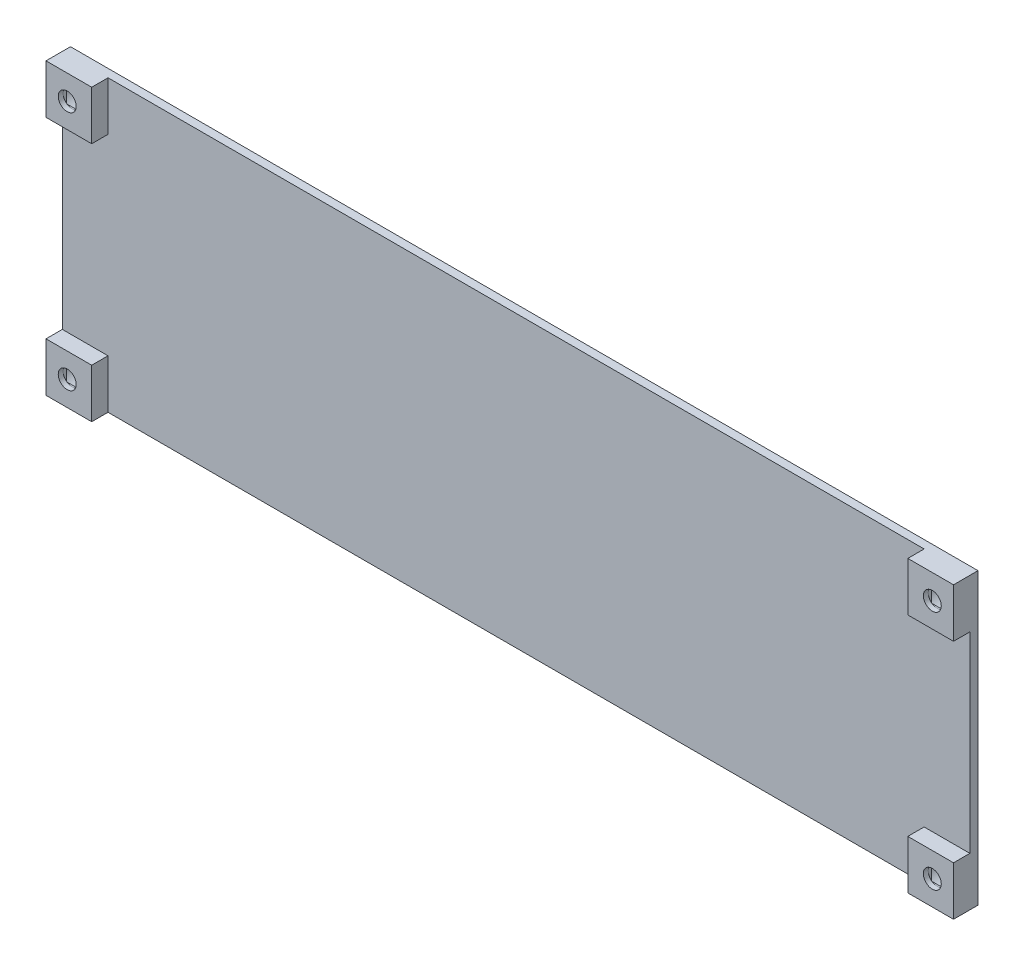
SolidWorks part; units mm, degrees
ref_plane "Front Plane" through (0, 0, 0) normal (0, 0, 1) x (1, 0, 0)
ref_plane "Top Plane" through (0, 0, 0) normal (0, 1, 0) x (1, 0, 0)
ref_plane "Right Plane" through (0, 0, 0) normal (1, 0, 0) x (0, 0, -1)
sketch "Sketch1" plane through (0, 0, 0) normal (0, 0, 1) x (1, 0, 0)
  line L1 (-56, -17.75) -> (56, -17.75)
  line L2 (-56, -17.75) -> (-56, 17.75)
  line L3 (-56, 17.75) -> (56, 17.75)
  line L4 (56, -17.75) -> (56, 17.75)
  line L5 (-56, -17.75) -> (56, 17.75) construction
  line L6 (-56, 17.75) -> (56, -17.75) construction
  point P0 (0, 0)
  dimension "D1" = 112
  dimension "D2" = 35.5
extrude "Boss-Extrude1" add sketch "Sketch1" along normal blind 1
sketch "Sketch2" plane through (0, 0, 1) normal (0, 0, 1) x (1, 0, 0)
  line L0 (0, -17.75) -> (0, 17.75) construction
  line L1 (-56, 17.75) -> (-50, 17.75)
  line L2 (-56, 17.75) -> (-56, 11.75)
  line L3 (-56, 11.75) -> (-50, 11.75)
  line L4 (-50, 17.75) -> (-50, 11.75)
  line L5 (-56, -17.75) -> (56, -17.75) construction
  line L6 (56, 17.75) -> (-56, 17.75) construction
  line L7 (-56, 0) -> (56, 0) construction
  line L8 (-56, 17.75) -> (-56, -17.75) construction
  line L9 (56, -17.75) -> (56, 17.75) construction
  line L10 (-50, -17.75) -> (-50, -11.75)
  line L11 (-56, -11.75) -> (-50, -11.75)
  line L12 (-56, -17.75) -> (-56, -11.75)
  line L13 (-56, -17.75) -> (-50, -17.75)
  line L14 (56, -17.75) -> (50, -17.75)
  line L15 (56, -17.75) -> (56, -11.75)
  line L16 (56, -11.75) -> (50, -11.75)
  line L17 (50, -17.75) -> (50, -11.75)
  line L18 (50, 17.75) -> (50, 11.75)
  line L19 (56, 11.75) -> (50, 11.75)
  line L20 (56, 17.75) -> (56, 11.75)
  line L21 (56, 17.75) -> (50, 17.75)
  dimension "D1" = 6
extrude "Boss-Extrude2" add sketch "Sketch2" along normal blind 2
sketch "Sketch3" plane through (0, 0, 3) normal (0, 0, 1) x (1, 0, 0)
  line L0 (-56, 0) -> (56, 0) construction
  line L1 (-56, 11.75) -> (-56, -11.75) construction
  line L2 (56, -11.75) -> (56, 11.75) construction
  line L3 (0, 17.75) -> (0, -17.75) construction
  line L4 (50, 17.75) -> (-50, 17.75) construction
  line L5 (-50, -17.75) -> (50, -17.75) construction
  line L6 (-56, 11.75) -> (-50, 17.75) construction
  line L7 (-56, -11.75) -> (-50, -17.75) construction
  line L8 (56, -11.75) -> (50, -17.75) construction
  line L9 (56, 11.75) -> (50, 17.75) construction
  circle A0 centre (-53, 14.75) radius 1.1
  circle A1 centre (-53, -14.75) radius 1.1
  circle A2 centre (53, -14.75) radius 1.1
  circle A3 centre (53, 14.75) radius 1.1
  dimension "D1" = 2.2
extrude "Cut-Extrude1" cut sketch "Sketch3" against normal through all
sketch "Sketch4" plane through (0, 0, 0) normal (0, 0, -1) x (-1, 0, 0)
  circle A0 centre (-53, 14.75) radius 2
  circle A1 centre (-53, -14.75) radius 2
  circle A2 centre (53, 14.75) radius 2
  circle A3 centre (53, -14.75) radius 2
  dimension "D1" = 4
extrude "Cut-Extrude2" cut sketch "Sketch4" against normal blind 2
sketch "Sketch5" plane through (0, 0, 2) normal (0, 0, -1) x (-1, 0, 0)
  line L2 (-54.1, 13.0797) -> (-54.1, 16.4203)
  line L4 (-51.9, 13.0797) -> (-51.9, 16.4203)
  line L5 (-54.1, 13.0797) -> (-51.9, 16.4203) construction
  line L6 (-54.1, 16.4203) -> (-51.9, 13.0797) construction
  circle A0 centre (-53, 14.75) radius 2 construction
  circle A1 centre (-53, 14.75) radius 1.1 construction
  circle A2 centre (-53, 14.75) radius 2 construction
  arc A3 (-51.9, 16.4203) -> (-54.1, 16.4203) centre (-53, 14.75) ccw
  arc A4 (-54.1, 13.0797) -> (-51.9, 13.0797) centre (-53, 14.75) ccw
  point P0 (-53, 14.75)
extrude "Cut-Extrude3" cut sketch "Sketch5" against normal blind 0.2
sketch "Sketch6" plane through (0, 0, 2.2) normal (0, 0, -1) x (-1, 0, 0)
  line L0 (-51.9, 13.0797) -> (-51.9, 16.4203) construction
  line L1 (-54.1, 13.65) -> (-51.9, 13.65)
  line L2 (-54.1, 13.65) -> (-54.1, 15.85)
  line L3 (-54.1, 15.85) -> (-51.9, 15.85)
  line L4 (-51.9, 13.65) -> (-51.9, 15.85)
  line L5 (-54.1, 13.65) -> (-51.9, 15.85) construction
  line L6 (-54.1, 15.85) -> (-51.9, 13.65) construction
  arc A0 (-51.9, 14.75) -> (-54.1, 14.75) centre (-53, 14.75) ccw construction
  point P0 (-53, 14.75)
extrude "Cut-Extrude4" cut sketch "Sketch6" against normal blind 0.2
mirror "Mirror1" about plane through (0, 0, 0) normal (1, 0, 0) of "Cut-Extrude4", "Cut-Extrude3"
mirror "Mirror2" about plane through (0, 0, 0) normal (0, 1, 0) of "Mirror1", "Cut-Extrude3", "Cut-Extrude4"
sketch "Sketch7" plane through (0, 0, 0) normal (0, 0, -1) x (-1, 0, 0)
  line L0 (56, -17.75) -> (-56, -17.75) construction
  line L1 (-56, 17.75) -> (-55.6, 17.75)
  line L2 (-56, 17.75) -> (-56, -17.75)
  line L3 (-56, -17.75) -> (-55.6, -17.75)
  line L4 (-55.6, 17.75) -> (-55.6, -17.75)
  line L6 (56, 17.75) -> (55.6, 17.75)
  line L7 (56, 17.75) -> (56, -17.75)
  line L8 (56, -17.75) -> (55.6, -17.75)
  line L9 (55.6, 17.75) -> (55.6, -17.75)
  dimension "D1" = 0.4
extrude "Cut-Extrude5" cut sketch "Sketch7" against normal through all
sketch "Sketch8" plane through (0, 0, 0) normal (0, 0, -1) x (-1, 0, 0)
  line L0 (-55.6, 17.75) -> (55.6, -17.75) construction
  line L1 (-12.5869, -14.75) -> (0, -14.75) construction
  line L2 (55.6, -17.75) -> (-55.6, -17.75) construction
  line L3 (0, 17.75) -> (0, -17.75) construction
  line L4 (-55.6, 17.75) -> (55.6, 17.75) construction
  text T0 "3\r\n" font "@HarmonyOS Sans SC" height 28
  dimension "D1" = 3
extrude "Cut-Extrude6" cut sketch "Sketch8" against normal blind 0.2
sketch "Sketch9" plane through (0, 0, 0.2) normal (0, 0, -1) x (-1, 0, 0)
  line L5 (-10.6681, 7.2148) -> (-6.6364, 4.9018)
  line L6 (-10.6681, 7.2148) -> (-6.6364, 4.9018)
  line L17 (-6.8262, -6.4083) -> (-11.0474, -8.8296)
  line L24 (-6.8262, -6.4083) -> (-11.0474, -8.8296)
  line L28 (-4.3415, 1.8283) -> (-4.3415, -2.5646)
  line L29 (-4.3415, 1.8283) -> (-4.3415, -2.5646)
  spline S6 degree 3 poles (240.9046, 1982.1907) (-43.9855, -42.6229) (-20.035, -1.4924) (-2.0637, -2.6172) (-1.7314, -2.6521) (-1.0713, -2.7522) (-0.7434, -2.8164) (-0.2568, -2.9479) (-0.0955, -2.9977) (0.2246, -3.1143) (0.3824, -3.1819) (0.6891, -3.3286) (0.8402, -3.4059) (1.1299, -3.5823) (1.2672, -3.684) (1.6613, -4.0189) (1.8904, -4.2712) (2.1652, -4.709) (2.2443, -4.8622) (2.374, -5.1771) (2.4239, -5.3401) (2.5037, -5.6737) (2.5361, -5.8433) (3.537, -14.8785) (-36.4997, -27.7136) (1995.4788, 159.9933) knots -6.467835 -6.467835 -6.467835 -6.467835 0.125 0.125 0.25 0.25 0.375 0.375 0.4375 0.4375 0.5 0.5 0.5625 0.5625 0.625 0.625 0.75 0.75 0.8125 0.8125 0.875 0.875 0.9375 0.9375 4.193329 4.193329 4.193329 4.193329 only from (-3.406, -2.5646) to (2.5811, -6.527)
  spline S7 degree 3 poles (-3.406, -2.5646) (-3.0692, -2.5696) (-2.7325, -2.5753) (-2.0637, -2.6172) (-1.7314, -2.6521) (-1.0713, -2.7522) (-0.7434, -2.8164) (-0.2568, -2.9479) (-0.0955, -2.9977) (0.2246, -3.1143) (0.3824, -3.1819) (0.6891, -3.3286) (0.8402, -3.4059) (1.1299, -3.5823) (1.2672, -3.684) (1.6613, -4.0189) (1.8904, -4.2712) (2.1652, -4.709) (2.2443, -4.8622) (2.374, -5.1771) (2.4239, -5.3401) (2.5037, -5.6737) (2.5361, -5.8433) (2.5738, -6.1837) (2.5775, -6.3553) (2.5811, -6.527) knots 0 0 0 0 0.125 0.125 0.25 0.25 0.375 0.375 0.4375 0.4375 0.5 0.5 0.5625 0.5625 0.625 0.625 0.75 0.75 0.8125 0.8125 0.875 0.875 0.9375 0.9375 1 1 1 1
  spline S8 degree 3 poles (1979.0375, -311.964) (-27.0173, 16.0388) (3.1924, 1.9668) (2.5576, -7.0571) (2.541, -7.1878) (2.4952, -7.4472) (2.4661, -7.5758) (2.3936, -7.8307) (2.3494, -7.9574) (2.2509, -8.2059) (2.1977, -8.3278) (2.0711, -8.56) (1.9963, -8.6695) (1.8371, -8.8828) (1.7528, -8.9876) (1.5726, -9.1835) (1.4765, -9.2747) (1.1753, -9.5331) (0.9546, -9.6866) (0.4909, -9.9453) (0.2483, -10.0511) (-0.256, -10.2205) (-0.516, -10.2827) (-12.2578, -11.8671) (-30.2208, 35.198) (229.0746, -1996.8604) knots -4.148886 -4.148886 -4.148886 -4.148886 0.0625 0.0625 0.125 0.125 0.1875 0.1875 0.25 0.25 0.3125 0.3125 0.375 0.375 0.4375 0.4375 0.5 0.5 0.625 0.625 0.75 0.75 0.875 0.875 6.35922 6.35922 6.35922 6.35922 only from (2.5811, -6.527) to (-1.5694, -10.3734)
  spline S9 degree 3 poles (2.5811, -6.527) (2.5786, -6.6601) (2.5761, -6.7932) (2.5576, -7.0571) (2.541, -7.1878) (2.4952, -7.4472) (2.4661, -7.5758) (2.3936, -7.8307) (2.3494, -7.9574) (2.2509, -8.2059) (2.1977, -8.3278) (2.0711, -8.56) (1.9963, -8.6695) (1.8371, -8.8828) (1.7528, -8.9876) (1.5726, -9.1835) (1.4765, -9.2747) (1.1753, -9.5331) (0.9546, -9.6866) (0.4909, -9.9453) (0.2483, -10.0511) (-0.256, -10.2205) (-0.516, -10.2827) (-1.0394, -10.3533) (-1.3044, -10.3634) (-1.5694, -10.3734) knots 0 0 0 0 0.0625 0.0625 0.125 0.125 0.1875 0.1875 0.25 0.25 0.3125 0.3125 0.375 0.375 0.4375 0.4375 0.5 0.5 0.625 0.625 0.75 0.75 0.875 0.875 1 1 1 1
  spline S10 degree 3 poles (301.9141, 1985.5505) (-29.8829, -33.2047) (-11.7404, 10.2377) (-0.9793, 8.8361) (-0.7595, 8.7856) (-0.327, 8.6433) (-0.1154, 8.5523) (0.2782, 8.3289) (0.4633, 8.1939) (0.804, 7.889) (0.9575, 7.7224) (1.2226, 7.3543) (1.3342, 7.15) (1.5054, 6.7292) (1.5672, 6.5104) (3.2042, -3.6175) (-44.1238, -17.7435) (1996.3925, 148.4302) knots -5.770818 -5.770818 -5.770818 -5.770818 0.125 0.125 0.25 0.25 0.375 0.375 0.5 0.5 0.625 0.625 0.75 0.75 0.875 0.875 6.321219 6.321219 6.321219 6.321219 only from (-1.8798, 8.9121) to (1.6626, 5.597)
  spline S11 degree 3 poles (-1.8798, 8.9121) (-1.653, 8.9033) (-1.4261, 8.8943) (-0.9793, 8.8361) (-0.7595, 8.7856) (-0.327, 8.6433) (-0.1154, 8.5523) (0.2782, 8.3289) (0.4633, 8.1939) (0.804, 7.889) (0.9575, 7.7224) (1.2226, 7.3543) (1.3342, 7.15) (1.5054, 6.7292) (1.5672, 6.5104) (1.6406, 6.0559) (1.6516, 5.8264) (1.6626, 5.597) knots 0 0 0 0 0.125 0.125 0.25 0.25 0.375 0.375 0.5 0.5 0.625 0.625 0.75 0.75 0.875 0.875 1 1 1 1
  spline S12 degree 3 poles (1970.5776, -344.8988) (-52.8993, 36.0895) (3.6936, 14.7515) (1.5487, 4.6338) (1.5102, 4.5005) (1.4154, 4.2373) (1.3587, 4.1067) (1.1686, 3.7323) (1.014, 3.5018) (0.7433, 3.1828) (0.6462, 3.0803) (0.4432, 2.8855) (0.3383, 2.7929) (0.1174, 2.6231) (0.0005, 2.5472) (-0.2415, 2.407) (-0.3665, 2.3409) (-0.6219, 2.2246) (-0.7523, 2.1759) (-1.0163, 2.0893) (-1.1494, 2.0501) (-1.553, 1.9467) (-1.8299, 1.9005) (-15.4247, 0.4346) (-32.0807, 50.4337) (87.372, -1995.9125) knots -4.489509 -4.489509 -4.489509 -4.489509 0.125 0.125 0.1875 0.1875 0.25 0.25 0.375 0.375 0.4375 0.4375 0.5 0.5 0.5625 0.5625 0.625 0.625 0.6875 0.6875 0.75 0.75 0.875 0.875 6.85413 6.85413 6.85413 6.85413 only from (1.6626, 5.597) to (-2.9466, 1.8283)
  spline S13 degree 3 poles (1.6626, 5.597) (1.6489, 5.3181) (1.6347, 5.0394) (1.5487, 4.6338) (1.5102, 4.5005) (1.4154, 4.2373) (1.3587, 4.1067) (1.1686, 3.7323) (1.014, 3.5018) (0.7433, 3.1828) (0.6462, 3.0803) (0.4432, 2.8855) (0.3383, 2.7929) (0.1174, 2.6231) (0.0005, 2.5472) (-0.2415, 2.407) (-0.3665, 2.3409) (-0.6219, 2.2246) (-0.7523, 2.1759) (-1.0163, 2.0893) (-1.1494, 2.0501) (-1.553, 1.9467) (-1.8299, 1.9005) (-2.3867, 1.8405) (-2.6665, 1.8329) (-2.9466, 1.8283) knots 0 0 0 0 0.125 0.125 0.1875 0.1875 0.25 0.25 0.375 0.375 0.4375 0.4375 0.5 0.5 0.5625 0.5625 0.625 0.625 0.6875 0.6875 0.75 0.75 0.875 0.875 1 1 1 1
  spline S14 degree 1 poles (1997.0524, 1.8283) (-2004.3265, 1.8283) knots -1433.786174 -1433.786174 1434.776193 1434.776193 only from (-2.9466, 1.8283) to (-4.3415, 1.8283)
  spline S15 degree 1 poles (-2.9466, 1.8283) (-4.3415, 1.8283) knots 0 0 1 1
  spline S16 degree 1 poles (-2004.3308, -2.5646) (1996.5877, -2.5646) knots -2137.848745 -2137.848745 2138.853396 2138.853396 only from (-4.3415, -2.5646) to (-3.406, -2.5646)
  spline S17 degree 1 poles (-4.3415, -2.5646) (-3.406, -2.5646) knots 0 0 1 1
  spline S24 degree 3 poles (-153.5974, -998.7445) (22.5739, 20.38) (7.0124, -11.6833) (-2.7402, -10.2681) (-3.0245, -10.1958) (-3.5856, -10.0101) (-3.8619, -9.8956) (-4.3834, -9.6265) (-4.6314, -9.4716) (-5.1018, -9.1205) (-5.3264, -8.9215) (-5.7298, -8.4896) (-5.9099, -8.2574) (-6.2359, -7.7675) (-6.3823, -7.5075) (-11.0503, 2.7023) (15.9587, 25.6148) (-943.3502, -356.9669) knots -3.956391 -3.956391 -3.956391 -3.956391 0.125 0.125 0.25 0.25 0.375 0.375 0.5 0.5 0.625 0.625 0.75 0.75 0.875 0.875 5.481589 5.481589 5.481589 5.481589 only from (-1.5694, -10.3734) to (-6.8262, -6.4083)
  spline S25 degree 3 poles (-1.5694, -10.3734) (-1.865, -10.3629) (-2.1605, -10.3522) (-2.7402, -10.2681) (-3.0245, -10.1958) (-3.5856, -10.0101) (-3.8619, -9.8956) (-4.3834, -9.6265) (-4.6314, -9.4716) (-5.1018, -9.1205) (-5.3264, -8.9215) (-5.7298, -8.4896) (-5.9099, -8.2574) (-6.2359, -7.7675) (-6.3823, -7.5075) (-6.6289, -6.9681) (-6.729, -6.6888) (-6.8262, -6.4083) knots 0 0 0 0 0.125 0.125 0.25 0.25 0.375 0.375 0.5 0.5 0.625 0.625 0.75 0.75 0.875 0.875 1 1 1 1
  spline S26 degree 3 poles (-905.3973, -456.191) (2.8123, 24.6712) (-15.413, 1.3388) (-10.6685, -9.7826) (-10.5581, -10.0124) (-10.2022, -10.6881) (-9.9304, -11.1198) (-9.4561, -11.7311) (-9.2879, -11.9281) (-8.9399, -12.3041) (-8.759, -12.4838) (-8.1906, -12.9925) (-7.7779, -13.2914) (-7.1237, -13.6979) (-6.8983, -13.8261) (-6.44, -14.0586) (-6.2068, -14.1644) (-5.499, -14.4598) (-5.014, -14.6226) (-4.0154, -14.8734) (-3.5067, -14.9614) (-2.7425, -15.0507) (-2.487, -15.073) (10.7145, -15.7522) (25.9311, 4.6024) (-70.9857, -1012.6845) knots -2.830229 -2.830229 -2.830229 -2.830229 0.0625 0.0625 0.125 0.125 0.25 0.25 0.3125 0.3125 0.375 0.375 0.5 0.5 0.5625 0.5625 0.625 0.625 0.75 0.75 0.875 0.875 0.9375 0.9375 4.09155 4.09155 4.09155 4.09155 only from (-11.0474, -8.8296) to (-1.4592, -15.1093)
  spline S27 degree 3 poles (-11.0474, -8.8296) (-10.9589, -9.0712) (-10.8692, -9.3122) (-10.6685, -9.7826) (-10.5581, -10.0124) (-10.2022, -10.6881) (-9.9304, -11.1198) (-9.4561, -11.7311) (-9.2879, -11.9281) (-8.9399, -12.3041) (-8.759, -12.4838) (-8.1906, -12.9925) (-7.7779, -13.2914) (-7.1237, -13.6979) (-6.8983, -13.8261) (-6.44, -14.0586) (-6.2068, -14.1644) (-5.499, -14.4598) (-5.014, -14.6226) (-4.0154, -14.8734) (-3.5067, -14.9614) (-2.7425, -15.0507) (-2.487, -15.073) (-1.974, -15.0994) (-1.7166, -15.1043) (-1.4592, -15.1093) knots 0 0 0 0 0.0625 0.0625 0.125 0.125 0.25 0.25 0.3125 0.3125 0.375 0.375 0.5 0.5 0.5625 0.5625 0.625 0.625 0.75 0.75 0.875 0.875 0.9375 0.9375 1 1 1 1
  spline S28 degree 3 poles (119.1164, -1007.808) (-33.8376, 4.3235) (-15.4611, -15.8731) (-0.2724, -15.0627) (0.0221, -15.0373) (0.8991, -14.9238) (1.4769, -14.8067) (2.6181, -14.4854) (3.1837, -14.2751) (3.9895, -13.8966) (4.5142, -13.6212) (5.0067, -13.2868) (5.4851, -12.9265) (5.7166, -12.7349) (6.1524, -12.3318) (6.3569, -12.1186) (6.7379, -11.6677) (6.9153, -11.4309) (7.2457, -10.936) (7.3989, -10.675) (7.6638, -10.1409) (7.7754, -9.8669) (7.9599, -9.3059) (8.0367, -9.0203) (8.1596, -8.4386) (8.2046, -8.1411) (9.306, 3.7451) (-19.4278, 17.4417) (1007.5853, -43.5367) knots -3.081956 -3.081956 -3.081956 -3.081956 0.0625 0.0625 0.125 0.125 0.25 0.25 0.375 0.375 0.4375 0.5 0.5 0.5625 0.5625 0.625 0.625 0.6875 0.6875 0.75 0.75 0.8125 0.8125 0.875 0.875 0.9375 0.9375 3.369619 3.369619 3.369619 3.369619 only from (-1.4592, -15.1093) to (8.2743, -6.947)
  spline S29 degree 3 poles (-1.4592, -15.1093) (-1.1618, -15.1018) (-0.8644, -15.0943) (-0.2724, -15.0627) (0.0221, -15.0373) (0.8991, -14.9238) (1.4769, -14.8067) (2.6181, -14.4854) (3.1837, -14.2751) (3.9895, -13.8966) (4.5142, -13.6212) (5.0067, -13.2868) (5.4851, -12.9265) (5.7166, -12.7349) (6.1524, -12.3318) (6.3569, -12.1186) (6.7379, -11.6677) (6.9153, -11.4309) (7.2457, -10.936) (7.3989, -10.675) (7.6638, -10.1409) (7.7754, -9.8669) (7.9599, -9.3059) (8.0367, -9.0203) (8.1596, -8.4386) (8.2046, -8.1411) (8.2598, -7.5455) (8.2677, -7.2463) (8.2743, -6.947) knots 0 0 0 0 0.0625 0.0625 0.125 0.125 0.25 0.25 0.375 0.375 0.4375 0.5 0.5 0.5625 0.5625 0.625 0.625 0.6875 0.6875 0.75 0.75 0.8125 0.8125 0.875 0.875 0.9375 0.9375 1 1 1 1
  spline S30 degree 3 poles (1000.4741, 117.6548) (-11.5766, -28.565) (8.7658, -15.8691) (8.2507, -6.1948) (8.2317, -6.0087) (8.1596, -5.4529) (8.0947, -5.085) (7.942, -4.5416) (7.8806, -4.3612) (7.7449, -4.0076) (7.671, -3.834) (7.5081, -3.4954) (7.4191, -3.3302) (7.2233, -3.0096) (7.117, -2.8539) (6.8929, -2.5489) (6.7737, -2.3999) (6.522, -2.1189) (6.3897, -1.9855) (5.9779, -1.6018) (5.6849, -1.3666) (5.0574, -0.9418) (4.7268, -0.7593) (4.2205, -0.5099) (4.0486, -0.4331) (-6.7363, 3.9986) (-23.2184, -3.6138) (413.0913, 912.0457) knots -3.100967 -3.100967 -3.100967 -3.100967 0.0625 0.0625 0.125 0.125 0.25 0.25 0.3125 0.3125 0.375 0.375 0.4375 0.4375 0.5 0.5 0.5625 0.5625 0.625 0.625 0.75 0.75 0.875 0.875 0.9375 0.9375 4.740191 4.740191 4.740191 4.740191 only from (8.2743, -6.947) to (3.3483, -0.152)
  spline S31 degree 3 poles (8.2743, -6.947) (8.2725, -6.7583) (8.2707, -6.5696) (8.2507, -6.1948) (8.2317, -6.0087) (8.1596, -5.4529) (8.0947, -5.085) (7.942, -4.5416) (7.8806, -4.3612) (7.7449, -4.0076) (7.671, -3.834) (7.5081, -3.4954) (7.4191, -3.3302) (7.2233, -3.0096) (7.117, -2.8539) (6.8929, -2.5489) (6.7737, -2.3999) (6.522, -2.1189) (6.3897, -1.9855) (5.9779, -1.6018) (5.6849, -1.3666) (5.0574, -0.9418) (4.7268, -0.7593) (4.2205, -0.5099) (4.0486, -0.4331) (3.6998, -0.2898) (3.5238, -0.2214) (3.3483, -0.152) knots 0 0 0 0 0.0625 0.0625 0.125 0.125 0.25 0.25 0.3125 0.3125 0.375 0.375 0.4375 0.4375 0.5 0.5 0.5625 0.5625 0.625 0.625 0.75 0.75 0.875 0.875 0.9375 0.9375 1 1 1 1
  spline S32 degree 3 poles (-907.787, 438.401) (10.6395, -29.5477) (-11.0689, -5.0082) (-6.2192, 5.9307) (-6.0917, 6.1758) (-5.8091, 6.6515) (-5.6547, 6.8825) (-5.3102, 7.3257) (-5.124, 7.5325) (-4.7187, 7.9115) (-4.498, 8.0844) (-4.0264, 8.3873) (-3.7803, 8.5148) (-3.2659, 8.7183) (-2.995, 8.7947) (6.244, 10.3141) (18.7048, -22.0907) (-78.3576, 1005.9701) knots -5.152903 -5.152903 -5.152903 -5.152903 0.125 0.125 0.25 0.25 0.375 0.375 0.5 0.5 0.625 0.625 0.75 0.75 0.875 0.875 4.917504 4.917504 4.917504 4.917504 only from (-6.6364, 4.9018) to (-1.8798, 8.9121)
  spline S33 degree 3 poles (-6.6364, 4.9018) (-6.541, 5.1637) (-6.4436, 5.4246) (-6.2192, 5.9307) (-6.0917, 6.1758) (-5.8091, 6.6515) (-5.6547, 6.8825) (-5.3102, 7.3257) (-5.124, 7.5325) (-4.7187, 7.9115) (-4.498, 8.0844) (-4.0264, 8.3873) (-3.7803, 8.5148) (-3.2659, 8.7183) (-2.995, 8.7947) (-2.4407, 8.8858) (-2.1603, 8.899) (-1.8798, 8.9121) knots 0 0 0 0 0.125 0.125 0.25 0.25 0.375 0.375 0.5 0.5 0.625 0.625 0.75 0.75 0.875 0.875 1 1 1 1
  spline S34 degree 3 poles (554.9953, -834.2287) (-30.7418, 9.3872) (-5.9633, -5.4235) (4.497, 0.4533) (4.7649, 0.6318) (5.2701, 1.0316) (5.5088, 1.2512) (5.8431, 1.6138) (5.9506, 1.7405) (6.1522, 1.9999) (6.247, 2.1331) (6.5134, 2.5437) (6.6666, 2.832) (6.9289, 3.4348) (7.0371, 3.7484) (7.2042, 4.3809) (7.2643, 4.7022) (8.5372, 16.5485) (-20.5997, 33.8912) (985.2829, -202.8634) knots -4.385193 -4.385193 -4.385193 -4.385193 0.125 0.125 0.25 0.25 0.375 0.375 0.4375 0.4375 0.5 0.5 0.625 0.625 0.75 0.75 0.875 0.875 5.282217 5.282217 5.282217 5.282217 only from (3.3483, -0.152) to (7.3557, 6.0173)
  spline S35 degree 3 poles (3.3483, -0.152) (3.6395, -0.0064) (3.9328, 0.1363) (4.497, 0.4533) (4.7649, 0.6318) (5.2701, 1.0316) (5.5088, 1.2512) (5.8431, 1.6138) (5.9506, 1.7405) (6.1522, 1.9999) (6.247, 2.1331) (6.5134, 2.5437) (6.6666, 2.832) (6.9289, 3.4348) (7.0371, 3.7484) (7.2042, 4.3809) (7.2643, 4.7022) (7.3345, 5.3557) (7.3451, 5.6871) (7.3557, 6.0173) knots 0 0 0 0 0.125 0.125 0.25 0.25 0.375 0.375 0.4375 0.4375 0.5 0.5 0.625 0.625 0.75 0.75 0.875 0.875 1 1 1 1
  spline S36 degree 3 poles (998.588, 138.1139) (-14.2645, -21.6168) (8.3109, -5.3882) (7.2904, 7.1054) (7.2549, 7.3741) (7.1514, 7.9061) (7.0842, 8.1695) (6.9176, 8.6908) (6.8178, 8.9494) (6.4768, 9.6946) (6.1944, 10.1593) (5.6904, 10.8096) (5.5086, 11.0178) (5.1261, 11.4068) (4.9242, 11.5888) (4.2871, 12.0983) (3.8194, 12.3955) (2.8469, 12.8913) (2.3391, 13.0896) (1.2869, 13.4009) (0.751, 13.5124) (-15.025, 15.5249) (-35.5781, -24.006) (81.514, 1010.2361) knots -2.755956 -2.755956 -2.755956 -2.755956 0.0625 0.0625 0.125 0.125 0.1875 0.1875 0.25 0.25 0.375 0.375 0.4375 0.4375 0.5 0.5 0.625 0.625 0.75 0.75 0.875 0.875 4.40557 4.40557 4.40557 4.40557 only from (7.3557, 6.0173) to (-1.4204, 13.6812)
  spline S37 degree 3 poles (7.3557, 6.0173) (7.3452, 6.2903) (7.3346, 6.5633) (7.2904, 7.1054) (7.2549, 7.3741) (7.1514, 7.9061) (7.0842, 8.1695) (6.9176, 8.6908) (6.8178, 8.9494) (6.4768, 9.6946) (6.1944, 10.1593) (5.6904, 10.8096) (5.5086, 11.0178) (5.1261, 11.4068) (4.9242, 11.5888) (4.2871, 12.0983) (3.8194, 12.3955) (2.8469, 12.8913) (2.3391, 13.0896) (1.2869, 13.4009) (0.751, 13.5124) (-0.3279, 13.65) (-0.874, 13.6669) (-1.4204, 13.6812) knots 0 0 0 0 0.0625 0.0625 0.125 0.125 0.1875 0.1875 0.25 0.25 0.375 0.375 0.4375 0.4375 0.5 0.5 0.625 0.625 0.75 0.75 0.875 0.875 1 1 1 1
  spline S38 degree 3 poles (-124.3737, 1006.0863) (26.7616, -5.8931) (10.5964, 14.3321) (-2.434, 13.6442) (-2.6853, 13.6221) (-3.4352, 13.5306) (-3.9294, 13.4345) (-4.9055, 13.1658) (-5.3914, 12.9971) (-6.3109, 12.5759) (-6.7508, 12.3294) (-7.5926, 11.767) (-7.994, 11.4444) (-8.5357, 10.9163) (-8.7071, 10.7322) (-9.0348, 10.3506) (-9.1911, 10.1531) (-9.6313, 9.5353) (-9.8861, 9.0883) (-10.2193, 8.4037) (-10.3229, 8.1721) (-14.6142, -2.8163) (5.1906, -24.3201) (-936.5866, 384.9023) knots -3.097344 -3.097344 -3.097344 -3.097344 0.0625 0.0625 0.125 0.125 0.25 0.25 0.375 0.375 0.5 0.5 0.625 0.625 0.6875 0.6875 0.75 0.75 0.875 0.875 0.9375 0.9375 3.777777 3.777777 3.777777 3.777777 only from (-1.4204, 13.6812) to (-10.6681, 7.2148)
  spline S39 degree 3 poles (-1.4204, 13.6812) (-1.6745, 13.6761) (-1.9286, 13.6709) (-2.434, 13.6442) (-2.6853, 13.6221) (-3.4352, 13.5306) (-3.9294, 13.4345) (-4.9055, 13.1658) (-5.3914, 12.9971) (-6.3109, 12.5759) (-6.7508, 12.3294) (-7.5926, 11.767) (-7.994, 11.4444) (-8.5357, 10.9163) (-8.7071, 10.7322) (-9.0348, 10.3506) (-9.1911, 10.1531) (-9.6313, 9.5353) (-9.8861, 9.0883) (-10.2193, 8.4037) (-10.3229, 8.1721) (-10.5077, 7.6989) (-10.5884, 7.4571) (-10.6681, 7.2148) knots 0 0 0 0 0.0625 0.0625 0.125 0.125 0.25 0.25 0.375 0.375 0.5 0.5 0.625 0.625 0.6875 0.6875 0.75 0.75 0.875 0.875 0.9375 0.9375 1 1 1 1
  dimension "D1" = 0.1
extrude "Boss-Extrude3" add sketch "Sketch9" along normal up to surface (0.2 mm away) up to face at (0, 0, 0)
